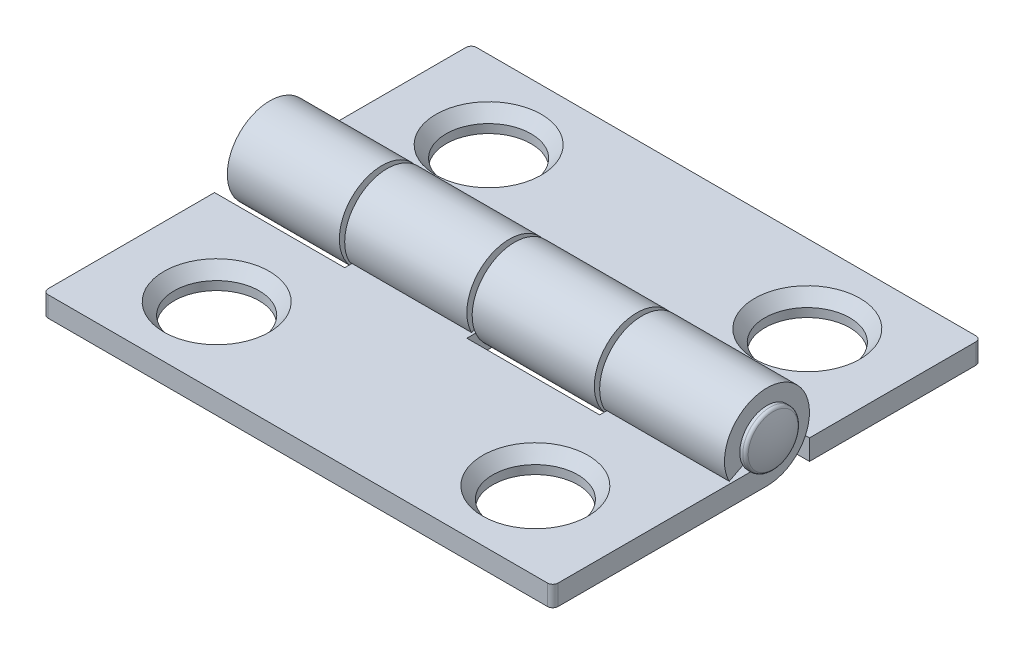
SolidWorks part; units mm, degrees
ref_plane "Front Plane" through (0, 0, 0) normal (0, 0, 1) x (1, 0, 0)
ref_plane "Top Plane" through (0, 0, 0) normal (0, 1, 0) x (1, 0, 0)
ref_plane "Right Plane" through (0, 0, 0) normal (1, 0, 0) x (0, 0, -1)
sketch "Sketch1" plane through (0, 0, 0) normal (0, 1, 0) x (1, 0, 0)
  line L0 (-19.05, 0) -> (19.05, 0) construction
  line L1 (-19.05, -16.002) -> (-19.05, 16.002) construction
  line L2 (11.9062, 10.16) -> (11.9062, -10.16) construction
  line L3 (-11.9062, -16.002) -> (11.9062, -16.002) construction
  line L4 (0, 0) -> (0, -16.002) construction
  line L5 (11.9062, -6.985) -> (11.9062, -13.335) construction
  line L7 (-11.9062, 10.16) -> (11.9062, 10.16) construction
  line L8 (-11.9062, 10.16) -> (-11.9062, -10.16) construction
  line L9 (-11.9062, -10.16) -> (11.9062, -10.16) construction
  line L10 (11.9062, 10.16) -> (11.9062, -10.16) construction
  line L11 (15.0813, -10.16) -> (8.7312, -10.16) construction
  line L12 (-11.9062, 10.16) -> (11.9062, -10.16) construction
  line L13 (-11.9062, -10.16) -> (11.9062, 10.16) construction
  circle A0 centre (11.9062, -10.16) radius 3.937 construction
  point P4 (0, 0)
  point P8 (-19.05, 0)
  point P10 (8.7312, 10.16)
  point P14 (15.0813, -10.16)
  point P18 (8.7312, -10.16)
  point P21 (11.9062, -10.16)
  point P25 (11.9063, 0)
  point P26 (11.9062, -10.16)
  point P27 (11.9062, -6.985)
  point P28 (11.9062, -13.335)
  point P29 (15.0813, 10.16)
  point P31 (-19.05, -16.002)
  point P32 (-11.9062, 10.16)
  point P33 (11.9062, -10.16)
  point P34 (-19.05, 16.002)
  point P38 (11.9062, -10.16)
  dimension "C'Sink Diameter" = 7.874
  dimension "Door Leaf Height" = 38.1
  dimension "Overall Width" = 32.004
  dimension "Hole Spacing" = 23.8125
  dimension "Hole Diameter" = 6.35
  dimension "Hole Spacing 2" = 20.32
  dimension "Frame Leaf Height" = 38.1
  dimension "Door Leaf Width" = 16.002
  dimension "Frame Leaf Width" = 16.002
  dimension "Hole Offset" = 7.1438
sketch "Sketch2" plane through (0, 0, 0) normal (1, 0, 0) x (0, 0, -1)
  line L2 (0, -3.175) -> (0, -1.651) construction
  line L4 (0, 1.651) -> (0, -1.651) construction
  circle A0 centre (0, 0) radius 3.175 construction
  circle A1 centre (0, 0) radius 2.032 construction
  point P8 (0, 0)
  dimension "Leaf OD" = 6.35
  dimension "Pin Head Diameter" = 4.064
  dimension "Leaf Thickness" = 1.524
  dimension "Pin Diameter" = 3.302
sketch "Sketch3" plane through (0, 0, 0) normal (1, 0, 0) x (0, 0, -1)
  line L3 (0, 0) -> (-3.175, -1.651) construction
  line L4 (0, -3.175) -> (-16.002, -3.175)
  line L5 (-16.002, -3.175) -> (-16.002, -1.651)
  line L7 (-16.002, -1.651) -> (0, -1.651)
  line L8 (-16.002, 0) -> (16.002, 0) construction
  line L9 (-1.4648, -0.7617) -> (-2.8169, -1.4648)
  line L11 (-3.175, 0) -> (-3.175, -1.651) construction
  circle A4 centre (0, 0) radius 1.651 construction
  circle A5 centre (0, 0) radius 3.175 construction
  arc A8 (-1.4648, -0.7617) -> (0, -1.651) centre (0, 0) cw
  arc A9 (-2.8169, -1.4648) -> (0, -3.175) centre (0, 0) cw
  point P0 (-2.8169, -1.4648)
  point P13 (-1.4648, -0.7617)
extrude "Boss-Extrude1" add sketch "Sketch3" along normal mid plane 38.1
sketch "Sketch4" plane through (0, 0, 0) normal (0, 1, 0) x (1, 0, 0)
  line L0 (-19.05, -3.175) -> (19.05, -3.175) construction
  line L1 (-19.05, -3.175) -> (19.05, -3.175) construction
  line L2 (19.05, 3.175) -> (-19.05, 3.175) construction
  line L3 (19.05, 3.175) -> (-19.05, 3.175) construction
  line L4 (0, -3.175) -> (0, 3.175)
  line L6 (0, 3.175) -> (9.525, 3.175)
  line L7 (9.525, -3.175) -> (0, -3.175)
  line L8 (9.525, 3.175) -> (9.525, -3.175)
  dimension "D1" = 9.525
extrude "Cut-Extrude1" cut sketch "Sketch4" against normal through all both and the other way through all
pattern_linear "LPattern1" count 2 spacing 19.05 along (-1, 0, 0) of "Cut-Extrude1"
sketch "Sketch5" plane through (0, -1.651, 0) normal (0, 1, 0) x (1, 0, 0)
  line L0 (-9.525, -3.175) -> (0, -3.175) construction
  line L1 (-9.525, 3.175) -> (-9.3266, 3.175)
  line L2 (-9.525, 3.175) -> (-9.525, -3.175)
  line L3 (-9.525, -3.175) -> (-9.3266, -3.175)
  line L4 (-9.3266, 3.175) -> (-9.3266, -3.175)
  line L5 (9.525, 3.175) -> (9.525, -3.175) construction
  line L6 (0, 3.175) -> (-0.1984, 3.175)
  line L7 (0, 3.175) -> (0, -3.175)
  line L8 (0, -3.175) -> (-0.1984, -3.175)
  line L9 (-0.1984, 3.175) -> (-0.1984, -3.175)
  line L10 (9.525, 3.175) -> (9.7234, 3.175)
  line L11 (9.525, 3.175) -> (9.525, -3.175)
  line L12 (9.525, -3.175) -> (9.7234, -3.175)
  line L13 (9.7234, 3.175) -> (9.7234, -3.175)
  line L14 (9.525, -3.175) -> (19.05, -3.175) construction
  line L15 (19.05, 3.175) -> (9.525, 3.175) construction
  dimension "D1" = 0.1984
extrude "Cut-Extrude2" cut sketch "Sketch5" against normal through all both and the other way through all
sketch "Sketch6" plane through (0, -1.651, 0) normal (0, 1, 0) x (1, 0, 0)
  line L0 (11.9062, -10.16) -> (-11.9062, -10.16) construction
  line L1 (11.9062, -10.16) -> (11.9062, -16.002) construction
  line L2 (-11.9062, -10.16) -> (-11.9062, -16.002) construction
  line L3 (11.9062, -10.16) -> (13.4938, -12.9096) construction
  circle A0 centre (11.9062, -10.16) radius 3.175
  circle A3 centre (-11.9062, -10.16) radius 3.175
  point P7 (13.4938, -12.9096)
  dimension "D1" = 30
extrude "Cut-Extrude3" cut sketch "Sketch6" against normal through all
sketch "Sketch7" plane through (0, -1.651, 0) normal (0, 1, 0) x (1, 0, 0)
  circle A0 centre (-11.9062, -10.16) radius 3.937
  circle A1 centre (11.9062, -10.16) radius 3.937
  circle A2 centre (11.9062, -10.16) radius 3.937 construction
extrude "Cut-Extrude4" cut sketch "Sketch7" against normal through all draft 41
fillet "Fillet1" radius 0.3969 2 edges at (19.05, -2.413, 16.002) (-19.05, -2.413, 16.002)
pattern_circular "CirPattern1" count 2 over 360 about axis through (0, 0, 0) along (0, 1, 0) of bodies 111 107
sketch "Sketch8" plane through (0, 0, 0) normal (1, 0, 0) x (0, 0, -1)
  circle A0 centre (0, 0) radius 1.651
  dimension "D1" = 3.302
extrude "Boss-Extrude2" add sketch "Sketch8" along normal mid plane 38.1 separate body
sketch "Sketch9" plane through (0, 0, 0) normal (0, 0, 1) x (1, 0, 0)
  line L2 (19.05, 2.032) -> (19.05, -2.032) construction
  line L3 (19.05, 0) -> (19.8438, 0) construction
  line L4 (0, -2.032) -> (0, 2.032) construction
  line L7 (19.05, 2.032) -> (19.05, 0)
  line L8 (19.05, 0) -> (19.8438, 0)
  line L9 (19.05, -1.651) -> (19.05, -3.175) construction
  line L10 (0, -2.032) -> (0, 2.032) construction
  line L11 (-19.05, 1.651) -> (-19.05, 3.175) construction
  line L12 (19.05, 2.032) -> (19.2729, 2.032)
  line L13 (19.05, 1.651) -> (19.05, 3.175) construction
  line L14 (-19.05, 0) -> (-19.8438, 0) construction
  line L15 (-19.05, 2.032) -> (-19.2729, 2.032)
  line L16 (-19.05, 0) -> (-19.8438, 0)
  line L17 (-19.05, 2.032) -> (-19.05, 0)
  line L21 (19.05, 1.651) -> (9.7234, 1.651) construction
  line L22 (19.05, 3.175) -> (9.7234, 3.175) construction
  line L24 (19.05, 0) -> (-19.05, 0) construction
  arc A0 (19.05, 2.032) -> (19.05, -2.032) centre (16.8459, 0) cw construction
  arc A4 (19.5112, 1.8658) -> (19.8438, 0) centre (14.4434, 0) cw
  arc A5 (19.2729, 2.032) -> (19.5112, 1.8658) centre (19.2729, 1.778) cw
  arc A8 (-19.2729, 2.032) -> (-19.5112, 1.8658) centre (-19.2729, 1.778) ccw
  arc A9 (-19.5112, 1.8658) -> (-19.8438, 0) centre (-14.4434, 0) ccw
  point P12 (19.05, 0)
  point P20 (19.4469, 0)
  point P29 (19.4469, 2.032)
  point P36 (19.05, 2.413)
  point P41 (-19.05, 2.413)
  point P42 (-19.4469, 2.032)
  point P43 (-19.4469, 0)
  dimension "D2" = 0.254
  dimension "D1" = 0.7937
revolve "Revolve1" add sketch "Sketch9" angle 360 about L24
sketch "Sketch10" plane through (0, -3.175, 0) normal (0, -1, 0) x (1, 0, 0)
  line L0 (0, -3.175) -> (9.525, -3.175) construction
  line L1 (-18.0975, -3.175) -> (-19.05, -3.175)
  line L2 (-18.0975, -3.175) -> (-18.0975, 3.175)
  line L3 (-18.0975, 3.175) -> (-19.05, 3.175)
  line L4 (-19.05, -3.175) -> (-19.05, 3.175)
  line L5 (-19.05, 3.175) -> (19.05, 3.175) construction
  dimension "D1" = 0.9525
extrude "Cut-Extrude5" cut sketch "Sketch10" against normal through all
chamfer "Chamfer1" distance 0.1651 angle 45 1 edges at (-19.05, 0, -1.651)
equation "\"D1@Boss-Extrude1\" = \"Door Leaf Height@Sketch1\""
equation "\"D1@Sketch4\"=\"Door Leaf Height@Sketch1\" / 4"
equation "\"D3@LPattern1\"= \"D1@Sketch4\" * 2"
equation "\"D1@Sketch8\" = \"Pin Diameter@Sketch2\""
equation "\"D1@Boss-Extrude2\" = \"Door Leaf Height@Sketch1\""
equation "\"D1@Sketch10\"=\"D1@Sketch4\"*.1"
equation "\"D1@Chamfer1\"=\"Pin Diameter@Sketch2\"*.05"
